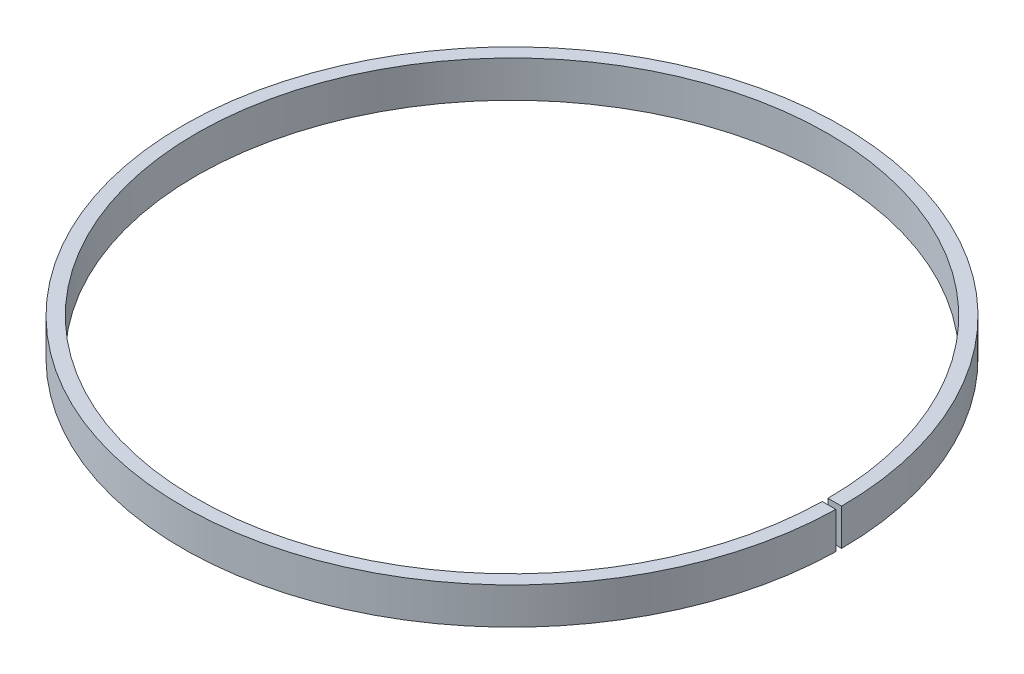
SolidWorks part; units mm, degrees
material "PTFE-15% Graphite Filled"
ref_plane "Front Plane" through (0, 0, 0) normal (0, 0, 1) x (1, 0, 0)
ref_plane "Top Plane" through (0, 0, 0) normal (0, 1, 0) x (1, 0, 0)
ref_plane "Right Plane" through (0, 0, 0) normal (1, 0, 0) x (0, 0, -1)
sketch "Sketch1" plane through (0, 0, 0) normal (0, 0, 1) x (1, 0, 0)
  line L0 (0, 0) -> (0, 49.3437) construction
  line L1 (54.7751, 0) -> (54.7751, 6.35)
  line L2 (54.7751, 0) -> (57.1373, 0)
  line L3 (54.7751, 6.35) -> (57.1373, 6.35)
  line L4 (57.1373, 0) -> (57.1373, 6.35)
  dimension "D1" = 2.3622
  dimension "D2" = 6.35
  dimension "D3" = 109.5502
revolve "Piston1" add sketch "Sketch1" angle 359 about L0
sketch "Sketch2" [suppressed] plane through (0, 0, 0) normal (0, 0, 1) x (1, 0, 0)
  line L0 (0, 0) -> (0, 102.7181) construction
  line L1 (28.5877, 6.35) -> (28.5877, 0)
  line L2 (28.5877, 6.35) -> (30.9499, 6.35)
  line L3 (28.5877, 0) -> (30.9499, 0)
  line L4 (30.9499, 6.35) -> (30.9499, 0)
  line L5 (54.7751, 6.35) -> (57.1373, 6.35) construction
  line L6 (57.1373, 0) -> (57.1373, 6.35) construction
  dimension "D1" = 61.8998
  dimension "D2" = 57.1754
revolve "Revolve1" [suppressed] add sketch "Sketch2" angle 359 about L0
sketch "Sketch3" [suppressed] plane through (0, 0, 0) normal (0, 0, 1) x (1, 0, 0)
  line L0 (0, 0) -> (0, 32.3824) construction
  line L1 (0, 0) -> (0, 49.3437) construction
  line L2 (45.2501, 6.35) -> (47.6123, 6.35)
  line L3 (45.2501, 6.35) -> (45.2501, 0)
  line L4 (47.6123, 6.35) -> (47.6123, 0)
  line L5 (45.2501, 0) -> (47.6123, 0)
  line L6 (54.7751, 6.35) -> (57.1373, 6.35) construction
  line L7 (57.1373, 0) -> (57.1373, 6.35) construction
  dimension "D1" = 90.5002
revolve "Revolve2" [suppressed] add sketch "Sketch3" angle 359 about L0
